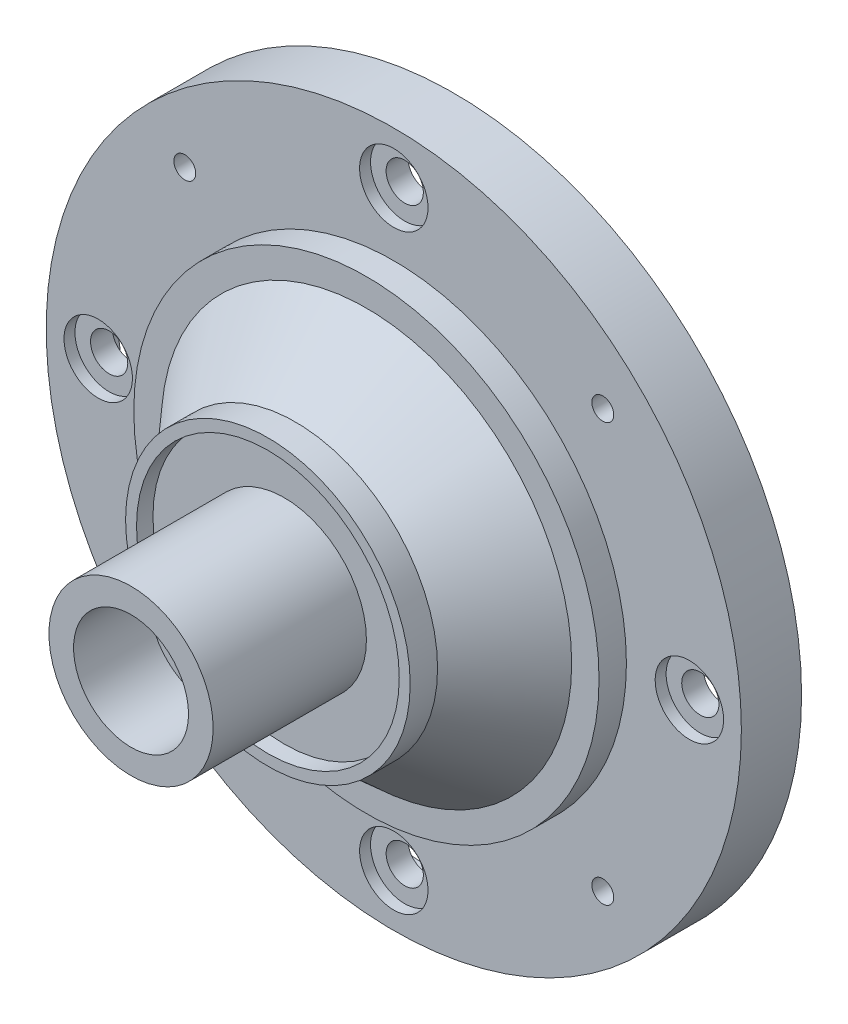
SolidWorks part; units mm, degrees
ref_plane "前视基准面" through (0, 0, 0) normal (0, 0, 1) x (1, 0, 0)
ref_plane "上视基准面" through (0, 0, 0) normal (0, 1, 0) x (1, 0, 0)
ref_plane "右视基准面" through (0, 0, 0) normal (1, 0, 0) x (0, 0, -1)
other "Configuration Table"
sketch "草图1" plane through (0, 0, 0) normal (1, 0, 0) x (0, 0, -1)
  line L0 (0, 10.5) -> (0, 15)
  line L1 (0, 15) -> (28, 15)
  line L2 (28, 15) -> (28, 24)
  line L3 (28, 24) -> (25, 24)
  line L4 (25, 24) -> (25, 26)
  line L5 (25, 26) -> (30, 26)
  line L6 (30, 26) -> (43, 37.5)
  line L7 (43, 37.5) -> (43, 42.5)
  line L8 (43, 42.5) -> (48, 42.5)
  line L11 (48, 42.5) -> (48, 63.5)
  line L12 (48, 63.5) -> (59, 63.5)
  line L13 (59, 63.5) -> (59, 61.5)
  line L14 (59, 61.5) -> (53, 61.5)
  line L15 (53, 61.5) -> (53, 40.5)
  line L16 (53, 40.5) -> (45, 40.5)
  line L17 (45, 40.5) -> (45, 37.5)
  line L18 (45, 37.5) -> (56, 37.5)
  line L19 (56, 37.5) -> (56, 35.5)
  line L20 (56, 35.5) -> (43.7577, 35.5)
  line L21 (43.7577, 35.5) -> (30, 23.3298)
  line L22 (30, 23.3298) -> (30, 12)
  line L23 (30, 12) -> (51, 12)
  line L24 (51, 12) -> (51, 8.5)
  line L25 (51, 8.5) -> (14, 8.5)
  line L26 (14, 8.5) -> (14, 10.5)
  line L27 (14, 10.5) -> (0, 10.5)
  line L28 (0, 0) -> (66.8392, 0) construction
  point P31 (59, 62.5)
  point P32 (49, 40.5)
  point P33 (0, 0)
  dimension "D1" = 21
  dimension "D2" = 30
  dimension "D3" = 48
  dimension "D4" = 52
  dimension "D5" = 75
  dimension "D6" = 85
  dimension "D7" = 59
  dimension "D8" = 43
  dimension "D9" = 10
  dimension "D10" = 5
  dimension "D11" = 2
  dimension "D13" = 2
  dimension "D14" = 5
  dimension "D15" = 25
  dimension "D16" = 2
  dimension "D17" = 2
  dimension "D18" = 3
  dimension "D19" = 127
  dimension "D20" = 123
  dimension "D21" = 75
  dimension "D22" = 71
  dimension "D23" = 24
  dimension "D24" = 17
  dimension "D25" = 14
  dimension "D26" = 51
  dimension "D27" = 13
revolve "旋转1" add sketch "草图1" angle 360 about L28
sketch "草图2" plane through (0, 0, -56) normal (0, 0, -1) x (-1, 0, 0)
  circle A1 centre (0, 0) radius 37.5
  circle A2 centre (0, 0) radius 37.5
  dimension "D1" = 0
sketch "草图3" plane through (0, 0, -56) normal (0, 0, -1) x (-1, 0, 0)
  line L0 (0, -35.5) -> (0, -37.5)
  line L1 (-5, -35.1461) -> (-5, -37.1652)
  line L2 (5, -35.1461) -> (5, -37.1652)
  line L3 (-5, -19.3632) -> (-5, -47.7078) construction
  line L4 (0, -19.3632) -> (0, -47.7078) construction
  line L5 (5, -19.3632) -> (5, -47.7078) construction
  circle A0 centre (0, 0) radius 35.5 construction
  circle A1 centre (0, 0) radius 37.5
  arc A2 (-5, -37.1652) -> (5, -37.1652) centre (0, 0) ccw
  arc A3 (-5, -35.1461) -> (5, -35.1461) centre (0, 0) ccw
  circle M4 centre (0, 0) radius 37.5
  circle M5 centre (0, 0) radius 35.5
  dimension "D1" = 0
  dimension "D2" = 5
  dimension "D3" = 5
extrude "凸台-拉伸1" add sketch "草图3" along normal blind 12 contours L1 L0 M5 M4 | L2 L0 M5 M4
pattern_circular "阵列(圆周)1" count 4 over 360 about axis through (0, 0, 0) along (0, 0, 1) of "凸台-拉伸1"
sketch "草图4" plane through (0, 0, 0) normal (0, 1, 0) x (1, 0, 0)
  line L0 (-11.9419, 50) -> (-35.6795, 50)
  line L1 (-10.5, 0) -> (10.5, 0) construction
  dimension "D1" = 50
rib "筋1" sketch "草图4" sketch "草图4" thickness 1 extrusion direction parallel to sketch draft on no parameters "D1"=1
pattern_circular "阵列(圆周)2" count 8 over 360 about axis through (0, 0, 0) along (0, 0, 1) of "筋1"
sketch "草图6" plane through (0, 0, -53) normal (0, 0, -1) x (-1, 0, 0)
  line L0 (0, 0) -> (0, 54)
  circle A0 centre (0, 0) radius 54
  circle A1 centre (0, 54) radius 3.4
  dimension "D1" = 108
  dimension "D2" = 6.8
extrude "切除-拉伸1" cut sketch "草图6" against normal through all both and the other way through all contours A0 A1 | L0 A1 A0 | A0 A1 L0
sketch "草图7" plane through (0, 0, -48) normal (0, 0, 1) x (1, 0, 0)
  circle A0 centre (0, 54) radius 6.25
  dimension "D1" = 12.5
extrude "切除-拉伸2" cut sketch "草图7" against normal blind 2
pattern_circular "阵列(圆周)3" count 4 over 360 about axis through (0, 0, 0) along (0, 0, 1) of "切除-拉伸2", "切除-拉伸1"
sketch "草图8" plane through (0, 0, -53) normal (0, 0, -1) x (-1, 0, 0)
  line L0 (0, 75.1254) -> (0, 0) construction
  line L1 (0, 0) -> (38.1838, 38.1838) construction
  circle A0 centre (0, 0) radius 54 construction
  circle A1 centre (38.1838, 38.1838) radius 2
  dimension "D2" = 4
  dimension "D1" = 45
extrude "切除-拉伸3" cut sketch "草图8" against normal through all
pattern_circular "阵列(圆周)4" count 4 over 360 about axis through (0, 0, 0) along (0, 0, 1) of "切除-拉伸3"
sketch "草图9" plane through (0, 0, -53) normal (0, 0, -1) x (-1, 0, 0)
  circle A0 centre (0, 54) radius 3.4 construction
  circle A1 centre (0, 54) radius 3.4
  circle A2 centre (0, 54) radius 5.25
  dimension "D1" = 10.5
extrude "凸台-拉伸2" add sketch "草图9" along normal blind 1
pattern_circular "阵列(圆周)5" count 4 over 360 about axis through (0, 0, 0) along (0, 0, 1) of "凸台-拉伸2"
sketch "草图10" plane through (0, 0, -48) normal (0, 0, 1) x (1, 0, 0)
  circle A0 centre (0, 0) radius 54
